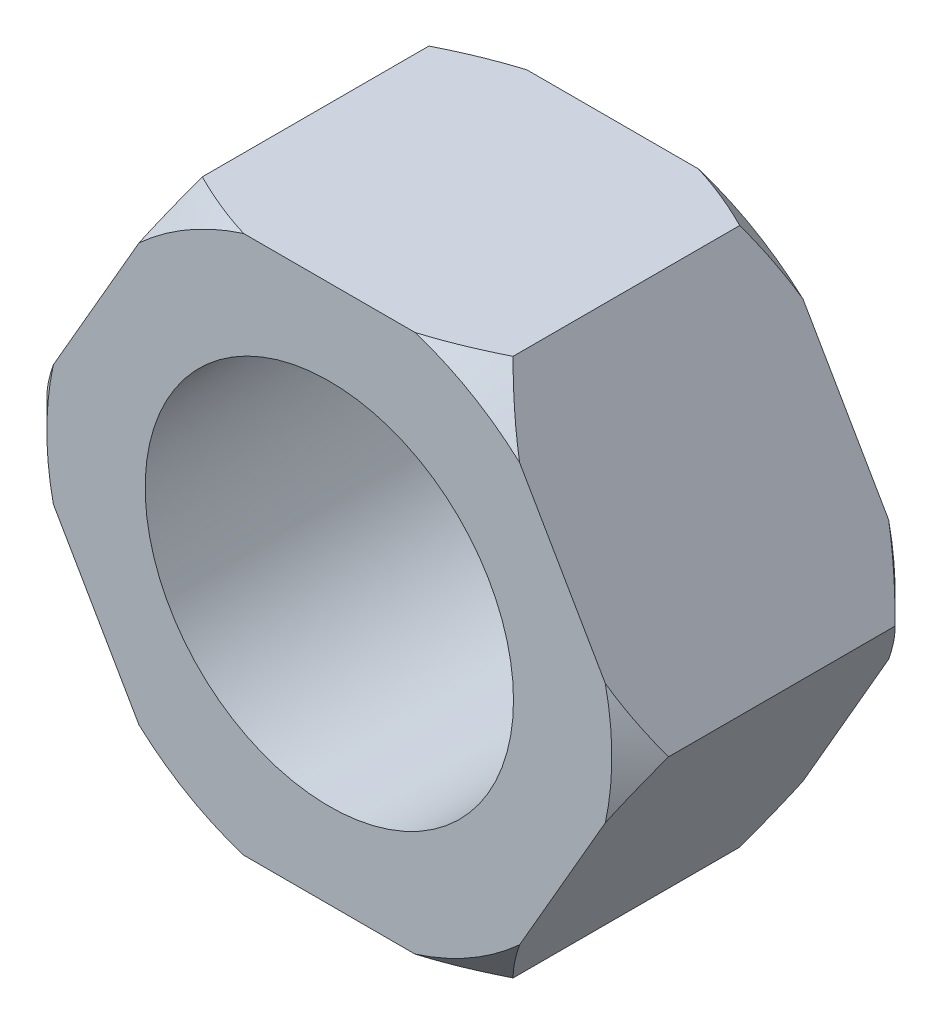
SolidWorks part; units mm, degrees
ref_plane "Front Plane" through (0, 0, 0) normal (0, 0, 1) x (1, 0, 0)
ref_plane "Top Plane" through (0, 0, 0) normal (0, 1, 0) x (1, 0, 0)
ref_plane "Right Plane" through (0, 0, 0) normal (1, 0, 0) x (0, 0, -1)
sketch "Sketch1" plane through (0, 0, 0) normal (0, 0, 1) x (1, 0, 0)
  line L1 (10.9697, 0) -> (5.4848, 9.5)
  line L2 (5.4848, 9.5) -> (-5.4848, 9.5)
  line L3 (-5.4848, 9.5) -> (-10.9697, 0)
  line L4 (-10.9697, 0) -> (-5.4848, -9.5)
  line L5 (-5.4848, -9.5) -> (5.4848, -9.5)
  line L6 (5.4848, -9.5) -> (10.9697, 0)
  circle A0 centre (0, 0) radius 6.5
  circle A1 centre (0, 0) radius 9.5 construction
  point P3 (-5.77, 9.6617)
  point P11 (0, 0)
  dimension "D1" = 13
  dimension "D2" = 19
extrude "Boss-Extrude1" add sketch "Sketch1" along normal blind 10
sketch "Sketch2" plane through (0, 0, 0) normal (0, 1, 0) x (0, 0, -1)
  line L0 (-9, 10.9697) -> (-10, 9.9697)
  line L3 (-1, 10.9697) -> (0, 9.9697)
  line L5 (0, 0) -> (-12.4496, 0) construction
  line L6 (-9, 10.9697) -> (-10, 10.9697)
  line L7 (-10, 10.9697) -> (-10, 9.9697)
  line L8 (-1, 10.9697) -> (0, 10.9697)
  line L9 (0, 10.9697) -> (0, 9.9697)
  line L11 (-10, 10.9697) -> (0, 10.9697) construction
  point P2 (0, 0)
  point P3 (0, 0)
  point P4 (-8.4617, -4.4848)
  point P5 (-8.4951, 3.3334)
  point P6 (0, 0)
  point P8 (0, 0)
  point P9 (0, 0)
  point P11 (0, 0)
  point P16 (-10, 9.4318)
  point P18 (0, 11.9697)
  point P19 (0, 0)
  point P20 (0, 0)
  point P21 (0, 0)
  point P22 (0, 0)
  point P23 (0, 0)
  point P24 (-10, -4.993)
  point P25 (-10, -4.993)
  point P26 (-10, -5.247)
  point P27 (0, 0)
  point P28 (0, 0)
  point P29 (-8.2693, -4.4848)
  point P30 (0, 7.3724)
  point P31 (0, 11.9697)
  point P32 (0, 11.9697)
  point P33 (0, 8.4326)
  point P34 (0, 0)
  point P36 (0, 0)
  point P37 (0, 0)
  point P38 (-3.1406, 10.9697)
  point P39 (0, 0)
  point P40 (0, 0)
  point P41 (1.6428, 10.9697)
  point P42 (0, 0)
  point P43 (0, 0)
  point P44 (0, 0)
  point P45 (-9.303, 10.7045)
  point P46 (0, 0)
  point P48 (-8.4784, 10.9697)
  point P51 (0, 0)
  point P52 (0, 0)
  point P53 (0, 0)
  point P54 (-10, 9.4321)
  point P55 (0, 0)
  point P56 (-11.5756, 10.9697)
  point P57 (0, 0)
  point P58 (1.1962, 10.9697)
  point P59 (-1.6408, 10.9697)
  point P60 (0, 0)
  dimension "D1" = 1
revolve "Cut-Revolve3" cut sketch "Sketch2" angle 360 about L5
